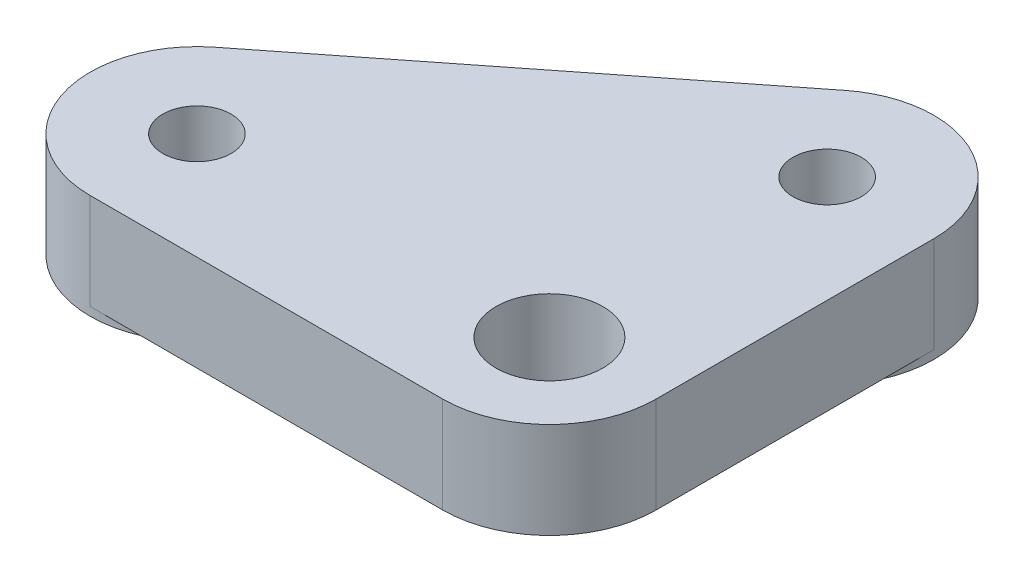
SolidWorks part; units mm, degrees
ref_plane "Front" through (0, 0, 0) normal (0, 0, 1) x (1, 0, 0)
ref_plane "Top" through (0, 0, 0) normal (0, 1, 0) x (1, 0, 0)
ref_plane "Right" through (0, 0, 0) normal (1, 0, 0) x (0, 0, -1)
sketch "Sketch1" plane through (0, 0, 0) normal (0, 1, 0) x (1, 0, 0)
  line L0 (0, 0) -> (16.5, 0) construction
  line L1 (16.5, 0) -> (0, 13) construction
  line L2 (0, 13) -> (0, 0) construction
  line L3 (-5, -5) -> (30.9254, -5)
  line L4 (30.9254, -5) -> (-5, 23.3048)
  line L5 (-5, 23.3048) -> (-5, -5)
  circle A0 centre (16.5, 0) radius 1.6
  circle A1 centre (0, 0) radius 2.5
  circle A2 centre (0, 13) radius 1.6
  dimension "D3" = 5
  dimension "D4" = 3.2
  dimension "D1" = 16.5
  dimension "D2" = 13
  dimension "D5" = 5
extrude "Boss-Extrude1" add sketch "Sketch1" along normal blind 1.57
fillet "Fillet1" radius 5 3 edges at (-5, 0.785, -23.3048) (-5, 0.785, 5) (30.9254, 0.785, 5)
other "Move Face1" [suppressed] parameters "D1"=0.0762
sketch "Sketch2" plane through (0, 1.57, 0) normal (0, 1, 0) x (1, 0, 0)
  line L3 (19.5944, 3.9275) -> (3.0944, 16.9275)
  line L4 (-5, 13) -> (-5, 0)
  line L5 (0, -5) -> (16.5, -5)
  line L6 (19.5944, 3.9275) -> (3.0944, 16.9275)
  line L7 (-5, 13) -> (-5, 0)
  line L8 (0, -5) -> (16.5, -5)
  circle A0 centre (0, 0) radius 2.5 construction
  circle A1 centre (16.5, 0) radius 1.6 construction
  circle A2 centre (0, 13) radius 1.6 construction
  arc A3 (3.0944, 16.9275) -> (-5, 13) centre (0, 13) ccw
  arc A4 (-5, 0) -> (0, -5) centre (0, 0) ccw
  arc A5 (16.5, -5) -> (19.5944, 3.9275) centre (16.5, 0) ccw
  arc A6 (3.0944, 16.9275) -> (-5, 13) centre (0, 13) ccw
  arc A7 (-5, 0) -> (0, -5) centre (0, 0) ccw
  arc A8 (16.5, -5) -> (19.5944, 3.9275) centre (16.5, 0) ccw
  circle A9 centre (0, 0) radius 2.5
  circle A10 centre (16.5, 0) radius 1.6
  circle A11 centre (0, 13) radius 1.6
  dimension "D1" = 0
extrude "Boss-Extrude2" add sketch "Sketch2" along normal blind 2.93
sketch "Sketch3" plane through (0, 0, 0) normal (0, -1, 0) x (1, 0, 0)
  circle A0 centre (16.5, 0) radius 5
  circle A1 centre (0, -13) radius 5
  circle A2 centre (0, -13) radius 1.6 construction
  circle A3 centre (16.5, 0) radius 1.6 construction
  circle A4 centre (0, -13) radius 1.6
  circle A5 centre (16.5, 0) radius 1.6
  arc A6 (19.5944, -3.9275) -> (16.5, 5) centre (16.5, 0) ccw construction
  arc A7 (-5, -13) -> (3.0944, -16.9275) centre (0, -13) ccw construction
extrude "Boss-Extrude3" add sketch "Sketch3" along normal blind 0.4
mirror "Mirror1" about plane through (-5, 1.57, -23.3048) normal (1, 0, 0) of bodies 104
delete or keep bodies "Body-Delete/Keep 1" type keep bodies bodies 105
